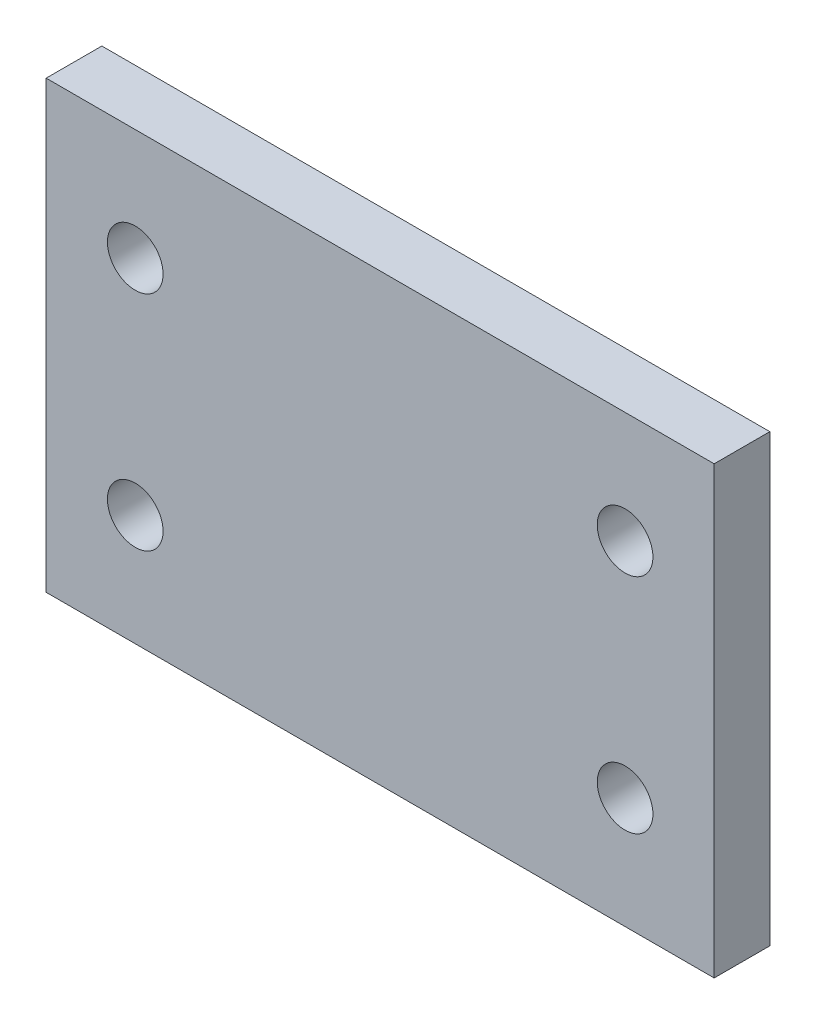
SolidWorks part; units mm, degrees
ref_plane "Front Plane" through (0, 0, 0) normal (0, 0, 1) x (1, 0, 0)
ref_plane "Top Plane" through (0, 0, 0) normal (0, 1, 0) x (1, 0, 0)
ref_plane "Right Plane" through (0, 0, 0) normal (1, 0, 0) x (0, 0, -1)
sketch "Sketch1" plane through (0, 0, 0) normal (0, 0, 1) x (1, 0, 0)
  line L1 (0, 0) -> (60, 0)
  line L2 (0, 0) -> (0, 40)
  line L3 (0, 40) -> (60, 40)
  line L4 (60, 0) -> (60, 40)
  dimension "D1" = 60
  dimension "D2" = 40
extrude "Boss-Extrude1" add sketch "Sketch1" along normal blind 5
sketch "Sketch2" plane through (0, 0, 5) normal (0, 0, 1) x (1, 0, 0)
  line L0 (60, 40) -> (0, 40) construction
  line L1 (0, 0) -> (60, 0) construction
  line L3 (0, 40) -> (0, 0) construction
  line L4 (60, 0) -> (60, 40) construction
  circle A0 centre (8, 30) radius 2.5
  circle A1 centre (8, 10) radius 2.5
  circle A2 centre (52, 10) radius 2.5
  circle A3 centre (52, 30) radius 2.5
  dimension "D1" = 5
  dimension "D2" = 5
  dimension "D3" = 5
  dimension "D4" = 5
  dimension "D5" = 10
  dimension "D6" = 10
  dimension "D7" = 10
  dimension "D8" = 10
  dimension "D9" = 8
  dimension "D10" = 8
  dimension "D11" = 8
  dimension "D12" = 8
extrude "Cut-Extrude1" cut sketch "Sketch2" against normal blind 10
